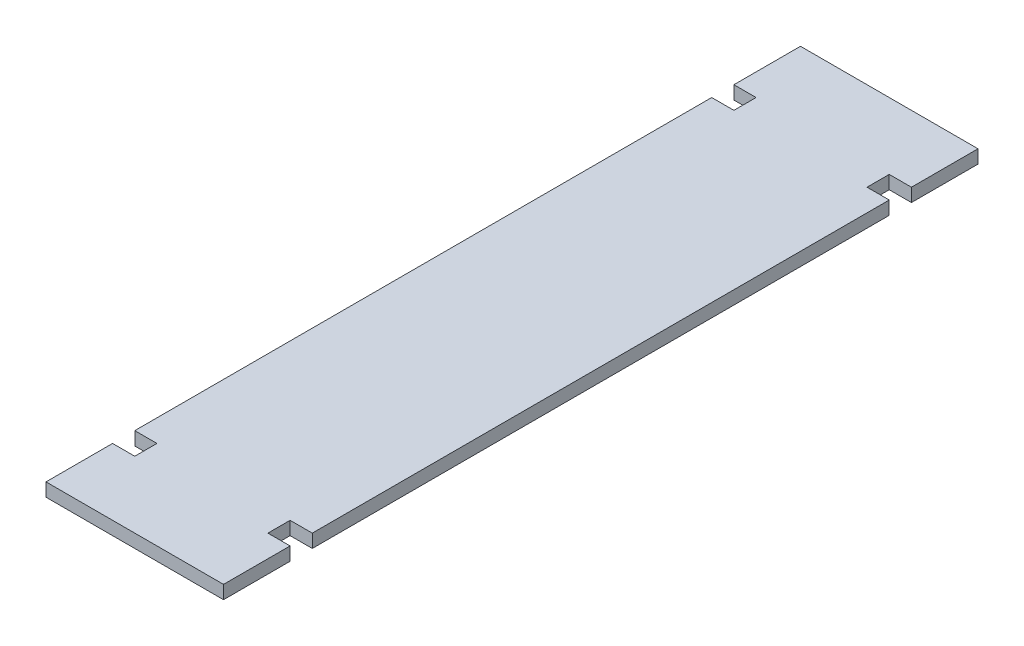
SolidWorks part; units mm, degrees
ref_plane "Front Plane" through (0, 0, 0) normal (0, 0, 1) x (1, 0, 0)
ref_plane "Top Plane" through (0, 0, 0) normal (0, 1, 0) x (1, 0, 0)
ref_plane "Right Plane" through (0, 0, 0) normal (1, 0, 0) x (0, 0, -1)
sketch "Sketch1" plane through (0, 0, 0) normal (0, 1, 0) x (1, 0, 0)
  line L1 (0, 0) -> (40, 0)
  line L2 (0, 0) -> (0, 170)
  line L3 (0, 170) -> (40, 170)
  line L4 (40, 0) -> (40, 170)
  dimension "D1" = 40
  dimension "D2" = 170
extrude "Boss-Extrude1" add sketch "Sketch1" along normal blind 3
sketch "Sketch2" plane through (0, 0, 0) normal (0, 1, 0) x (1, 0, 0)
  line L0 (0, 155) -> (5, 155)
  line L1 (0, 170) -> (0, 0) construction
  line L2 (5, 155) -> (5, 150)
  line L3 (5, 150) -> (0, 150)
  line L4 (0, 155) -> (0, 150)
  line L5 (20, 170) -> (20, 0)
  line L6 (40, 170) -> (0, 170) construction
  line L7 (0, 0) -> (40, 0) construction
  line L8 (0, 85) -> (40, 85)
  line L9 (40, 0) -> (40, 170) construction
  line L10 (40, 155) -> (40, 150)
  line L11 (35, 155) -> (35, 150)
  line L12 (40, 155) -> (35, 155)
  line L13 (35, 150) -> (40, 150)
  line L14 (35, 20) -> (40, 20)
  line L15 (40, 15) -> (35, 15)
  line L16 (35, 15) -> (35, 20)
  line L17 (40, 15) -> (40, 20)
  line L18 (0, 15) -> (0, 20)
  line L19 (5, 20) -> (0, 20)
  line L20 (5, 15) -> (5, 20)
  line L21 (0, 15) -> (5, 15)
  dimension "D1" = 5
  dimension "D2" = 5
  dimension "D3" = 15
extrude "Cut-Extrude1" cut sketch "Sketch2" along normal blind 10 contours L0 L4 L3 L2 | L15 L17 L14 L16 | L18 L21 L20 L19 | L11 L13 L10 L12
sketch "Sketch3" plane through (0, 0, 0) normal (0, 1, 0) x (1, 0, 0)
  line L0 (5, 150) -> (35, 150)
  line L1 (31.25, 168.5) -> (31.25, 150)
  line L2 (20, 150) -> (27.5002, 150)
  line L3 (20, 150) -> (20, 168.5)
  line L4 (8.75, 168.5) -> (31.25, 168.5)
  line L5 (8.75, 168.5) -> (8.75, 150)
  line L6 (0, 85) -> (40, 85)
  line L7 (0, 150) -> (0, 20) construction
  line L8 (40, 20) -> (40, 150) construction
  line L9 (8.75, 1.5) -> (31.25, 1.5)
  line L10 (31.25, 1.5) -> (31.25, 20)
  line L11 (8.75, 1.5) -> (8.75, 20)
  line L12 (5, 20) -> (35, 20)
  circle A1 centre (20, 159.25) radius 11.9086
  circle A2 centre (20, 10.75) radius 11.9086
  dimension "D1" = 18.5
  dimension "D3" = 11.25
extrude "Cut-Extrude2" [suppressed] cut sketch "Sketch3" along normal blind 10 contours L0 A1 L1 L4 L3 | L1 A1 | L5 A1 | L4 A1 L5 L0 L3 | A2 L9 L10 L12 L11 | A2 L11 | A2 L10
